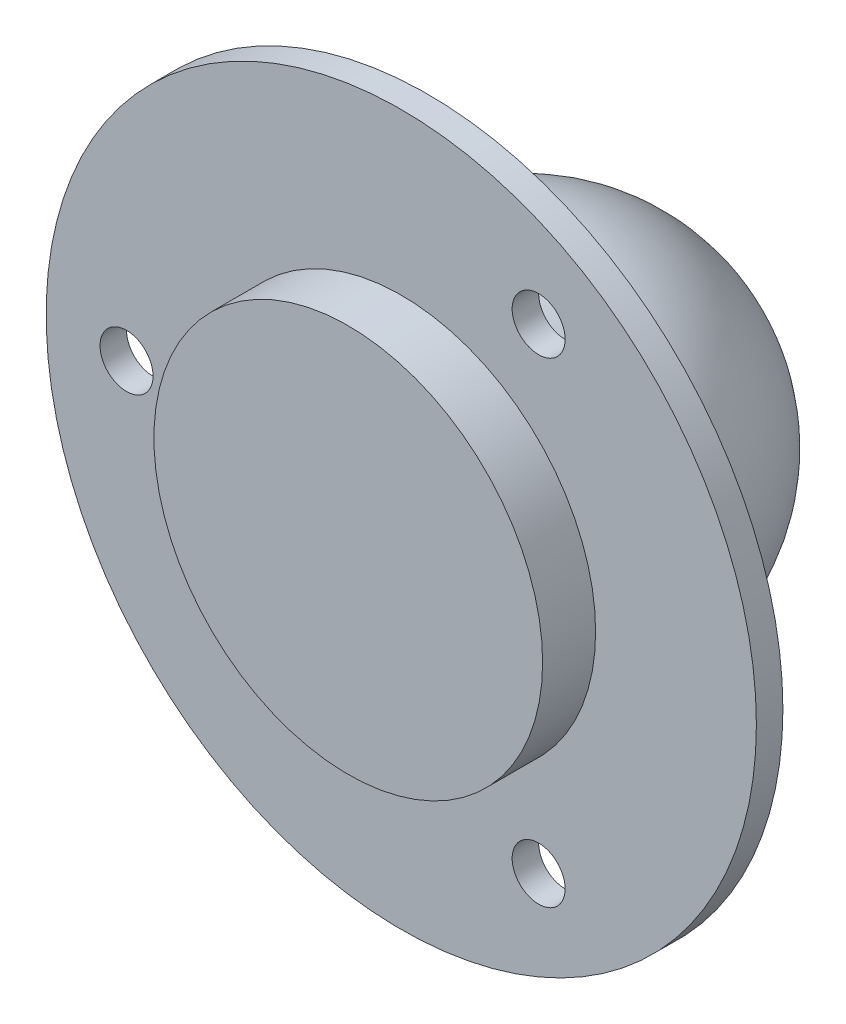
SolidWorks part; units mm, degrees
ref_plane "Front Plane" through (0, 0, 0) normal (0, 0, 1) x (1, 0, 0)
ref_plane "Top Plane" through (0, 0, 0) normal (0, 1, 0) x (1, 0, 0)
ref_plane "Right Plane" through (0, 0, 0) normal (1, 0, 0) x (0, 0, -1)
sketch "Sketch2" plane through (0, 0, 0) normal (0, 0, 1) x (1, 0, 0)
  circle A0 centre (0, 0) radius 20.1
  dimension "D1" = 40.2
extrude "Boss-Extrude1" add sketch "Sketch2" along normal blind 1.5
sketch "Sketch3" plane through (0, 0, 1.5) normal (0, 0, 1) x (1, 0, 0)
  circle A0 centre (0, 0) radius 11
  dimension "D1" = 22
extrude "Boss-Extrude2" add sketch "Sketch3" along normal blind 3 and the other way blind 18
sketch "Sketch4" plane through (0, 0, 1.5) normal (0, 0, 1) x (1, 0, 0)
  circle A3 centre (-15.55, 0) radius 1.5
  circle A4 centre (7.775, 13.4667) radius 1.5
  circle A5 centre (7.775, -13.4667) radius 1.5
  point P6 (0, 0)
  dimension "D1" = 3
  dimension "D2" = 3
extrude "Cut-Extrude1" cut sketch "Sketch4" against normal through all
fillet "Fillet2" radius 11 1 edges at (11, 0, -16.5)
